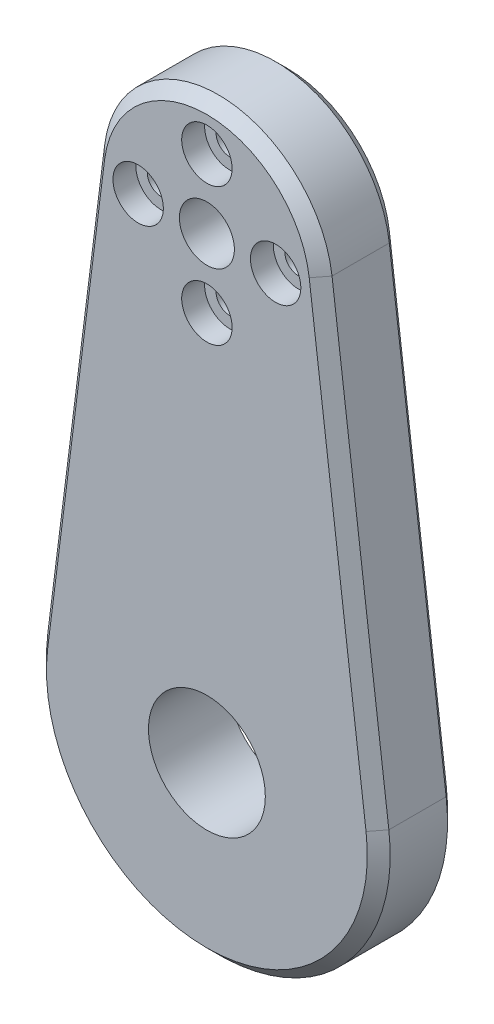
SolidWorks part; units mm, degrees
ref_plane "Front" through (0, 0, 0) normal (0, 0, 1) x (1, 0, 0)
ref_plane "Top" through (0, 0, 0) normal (0, 1, 0) x (1, 0, 0)
ref_plane "Right" through (0, 0, 0) normal (1, 0, 0) x (0, 0, -1)
sketch "Sketch1" plane through (0, 0, 0) normal (0, 0, 1) x (1, 0, 0)
  line L0 (0, 0) -> (0, -40) construction
  line L1 (-14.8824, -38.125) -> (-9.9216, 1.25)
  line L2 (14.8824, -38.125) -> (9.9216, 1.25)
  arc A0 (9.9216, 1.25) -> (-9.9216, 1.25) centre (0, 0) ccw
  arc A1 (-14.8824, -38.125) -> (14.8824, -38.125) centre (0, -40) ccw
  circle A2 centre (0, 0) radius 2.4
  circle A3 centre (0, -40) radius 5.1
  dimension "D1" = 20
  dimension "D2" = 4.8
  dimension "D3" = 15
  dimension "D5" = 10.2
  dimension "D4" = 40
extrude "Boss-Extrude1" add sketch "Sketch1" along normal blind 7
hole_wizard "CBORE for M2 SHCS1" positions "Sketch3" profile "Sketch4" counterbore size "M2" standard "ANSI Metric" end condition through all
sketch "Sketch3" plane through (0, 0, 7) normal (0, 0, 1) x (1, 0, 0)
  line L0 (0, 0) -> (0, 6) construction
  point P0 (0, 6)
  point P5 (6, 0)
  point P6 (0, -6)
  point P7 (-6, 0)
  point P10 (12.7584, -1.5025)
  point P11 (0, 0)
  dimension "D2" = 12
  dimension "D1" = 4
sketch "Sketch4" plane through (0, 6, 7) normal (1, 0, 0) x (0, -1, 0)
  line L0 (0, 0) -> (0, 7)
  line L1 (0, 7) -> (1.2, 7)
  line L3 (1.2, 7) -> (1.2, 2)
  line L4 (1.2, 2) -> (2.2, 2)
  line L5 (2.2, 2) -> (2.2, 0)
  line L7 (2.2, 0) -> (0, 0)
  line L11 (0, -6.35) -> (0, 107.95) construction
  dimension "Thru Hole Dia." = 2.4
  dimension "Thru Hole Depth" = 7
  dimension "C'Bore Dia." = 4.4
  dimension "C'Bore Depth" = 2
chamfer "Chamfer1" distance 1 angle 45 8 edges at (12.402, -18.4375, 0) (0, 10, 0) (0, -55, 0) (-12.402, -18.4375, 0) (12.402, -18.4375, 7) (0, 10, 7) (0, -55, 7) (-12.402, -18.4375, 7)
